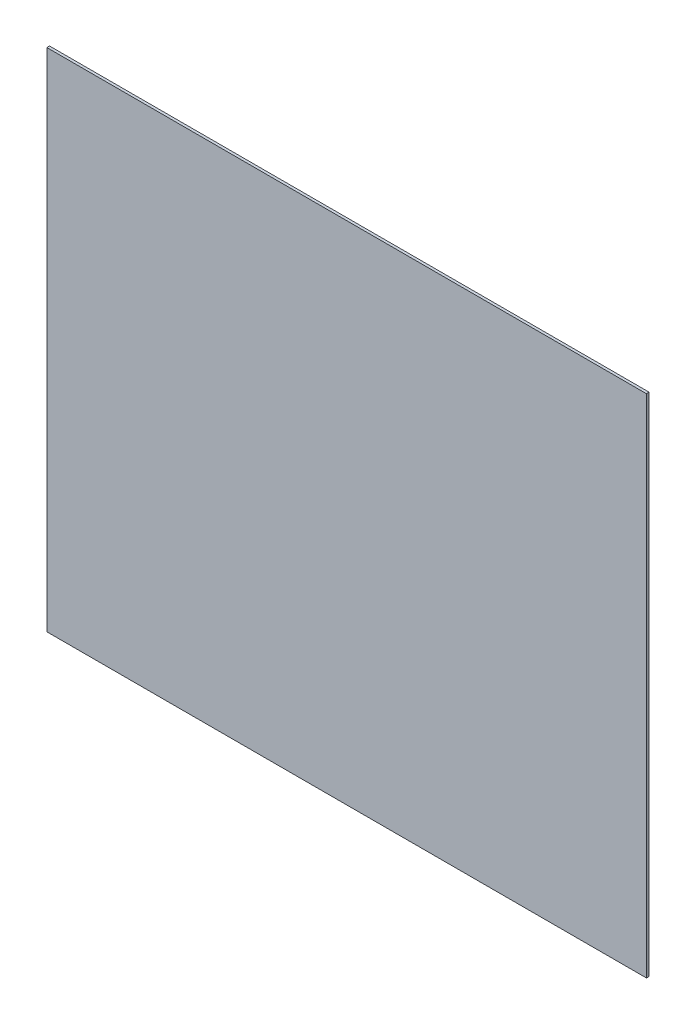
SolidWorks part; units mm, degrees
material "Pine"
ref_plane "Front Plane" through (0, 0, 0) normal (0, 0, 1) x (1, 0, 0)
ref_plane "Top Plane" through (0, 0, 0) normal (0, 1, 0) x (1, 0, 0)
ref_plane "Right Plane" through (0, 0, 0) normal (1, 0, 0) x (0, 0, -1)
sketch "Sketch1" plane through (0, 0, 0) normal (0, 0, 1) x (1, 0, 0)
  line L1 (337.7, -285) -> (-337.7, -285)
  line L2 (337.7, -285) -> (337.7, 285)
  line L3 (337.7, 285) -> (-337.7, 285)
  line L4 (-337.7, -285) -> (-337.7, 285)
  line L5 (337.7, -285) -> (-337.7, 285) construction
  line L6 (337.7, 285) -> (-337.7, -285) construction
  point P0 (0, 0)
extrude "Boss-Extrude1" add sketch "Sketch1" along normal blind 3
